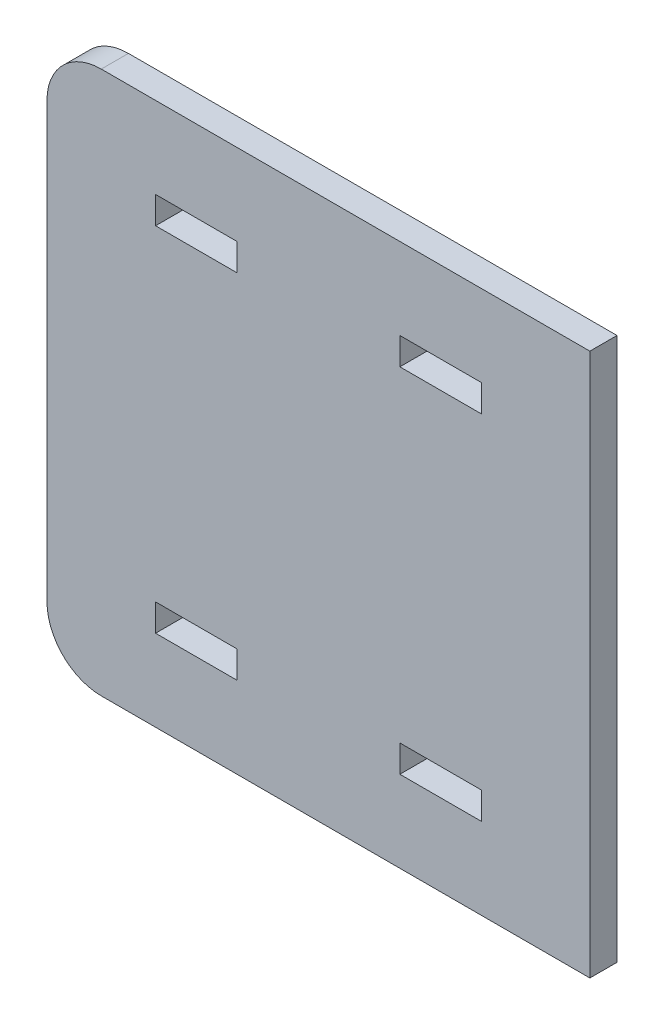
SolidWorks part; units mm, degrees
ref_plane "Front Plane" through (0, 0, 0) normal (0, 0, 1) x (1, 0, 0)
ref_plane "Top Plane" through (0, 0, 0) normal (0, 1, 0) x (1, 0, 0)
ref_plane "Right Plane" through (0, 0, 0) normal (1, 0, 0) x (0, 0, -1)
sketch "Sketch1" plane through (0, 0, 0) normal (0, 0, 1) x (1, 0, 0)
  line L0 (0, 50) -> (127.5197, 50) construction
  line L1 (0, 0) -> (100, 0)
  line L2 (0, 0) -> (0, 100)
  line L3 (0, 100) -> (100, 100)
  line L4 (100, 0) -> (100, 100)
  line L5 (80, 80) -> (80, 85)
  line L6 (20, 20) -> (35, 20)
  line L7 (20, 20) -> (20, 15)
  line L8 (20, 15) -> (35, 15)
  line L9 (35, 20) -> (35, 15)
  line L10 (65, 20) -> (80, 20)
  line L11 (65, 20) -> (65, 15)
  line L12 (65, 15) -> (80, 15)
  line L13 (80, 20) -> (80, 15)
  line L14 (65, 85) -> (80, 85)
  line L15 (65, 80) -> (65, 85)
  line L16 (65, 80) -> (80, 80)
  line L17 (35, 80) -> (35, 85)
  line L18 (20, 85) -> (35, 85)
  line L19 (20, 80) -> (20, 85)
  line L20 (20, 80) -> (35, 80)
  dimension "D1" = 100
  dimension "D2" = 100
  dimension "D3" = 15
  dimension "D4" = 15
  dimension "D5" = 5
  dimension "D6" = 30
  dimension "D7" = 20
  dimension "D8" = 60
extrude "Boss-Extrude1" add sketch "Sketch1" along normal blind 5
fillet "Fillet1" radius 10 2 edges at (0, 0, 2.5) (0, 100, 2.5)
